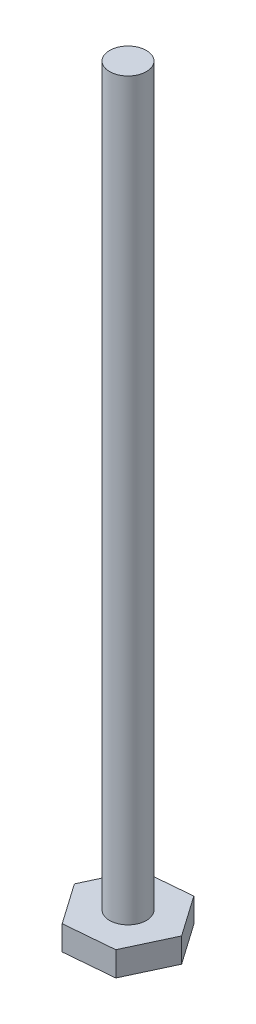
SolidWorks part; units mm, degrees
ref_plane "Front Plane" through (0, 0, 0) normal (0, 0, 1) x (1, 0, 0)
ref_plane "Top Plane" through (0, 0, 0) normal (0, 1, 0) x (1, 0, 0)
ref_plane "Right Plane" through (0, 0, 0) normal (1, 0, 0) x (0, 0, -1)
sketch "Sketch1" plane through (0, 0, 0) normal (0, 1, 0) x (1, 0, 0)
  line L1 (2.3159, -3.3121) -> (4.0263, 0.3496)
  line L2 (4.0263, 0.3496) -> (1.7104, 3.6617)
  line L3 (1.7104, 3.6617) -> (-2.3159, 3.3121)
  line L4 (-2.3159, 3.3121) -> (-4.0263, -0.3496)
  line L5 (-4.0263, -0.3496) -> (-1.7104, -3.6617)
  line L6 (-1.7104, -3.6617) -> (2.3159, -3.3121)
  circle A0 centre (0, 0) radius 3.5 construction
  dimension "D1" = 7
extrude "Boss-Extrude1" add sketch "Sketch1" along normal blind 2
sketch "Sketch2" plane through (0, 2, 0) normal (0, 1, 0) x (1, 0, 0)
  circle A0 centre (0, 0) radius 1.5
  dimension "D1" = 3
extrude "Boss-Extrude2" add sketch "Sketch2" along normal blind 60
